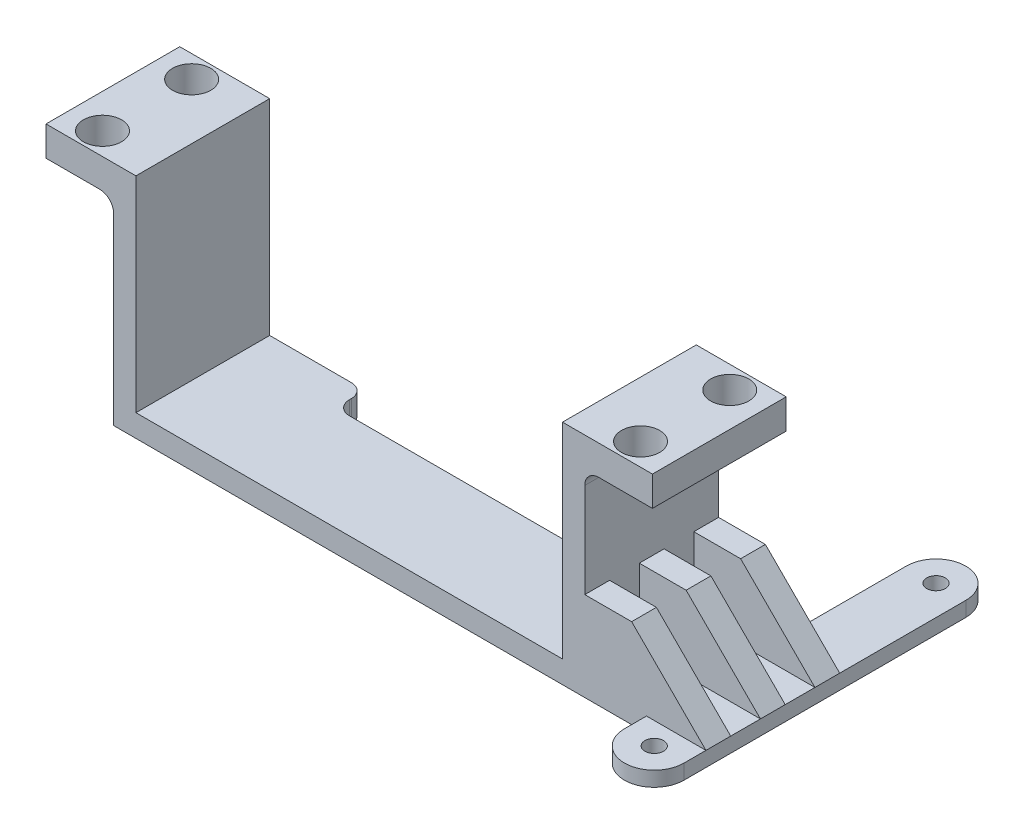
SolidWorks part; units mm, degrees
ref_plane "Front Plane" through (0, 0, 0) normal (0, 0, 1) x (1, 0, 0)
ref_plane "Top Plane" through (0, 0, 0) normal (0, 1, 0) x (1, 0, 0)
ref_plane "Right Plane" through (0, 0, 0) normal (1, 0, 0) x (0, 0, -1)
sketch "Sketch1" plane through (0, 0, 0) normal (0, 0, 1) x (1, 0, 0)
  line L0 (-3.81, 35.052) -> (0, 35.052)
  line L1 (0, 0) -> (72.898, 0)
  line L2 (0, 0) -> (0, 35.052)
  line L4 (72.898, 0) -> (72.898, 35.052)
  line L6 (-3.81, 35.052) -> (-3.81, -3.81)
  line L7 (-3.81, -3.81) -> (76.708, -3.81)
  line L8 (76.708, 35.052) -> (76.708, -3.81)
  line L9 (72.898, 35.052) -> (76.708, 35.052)
  dimension "D1" = 3.81
  dimension "D2" = 3.81
  dimension "D3" = 3.81
  dimension "D4" = 38.862
  dimension "D5" = 72.898
extrude "Boss-Extrude1" add sketch "Sketch1" along normal blind 22.86
sketch "Sketch2" plane through (0, -3.81, 0) normal (0, -1, 0) x (1, 0, 0)
  line L0 (92.329, 26.6192) -> (92.329, -21.5392) construction
  line L2 (87.249, 26.6192) -> (87.249, 22.86)
  line L3 (97.409, 26.6192) -> (97.409, -21.5392)
  line L4 (-3.81, 22.86) -> (76.708, 22.86) construction
  line L5 (76.708, 22.86) -> (76.708, 0) construction
  line L6 (76.708, 22.86) -> (87.249, 22.86)
  line L7 (76.708, 22.86) -> (76.708, 0)
  line L8 (76.708, 0) -> (87.249, 0)
  line L9 (87.249, 0) -> (87.249, -21.5392)
  circle A0 centre (92.329, 26.6192) radius 1.5875
  circle A1 centre (92.329, -21.5392) radius 1.5875
  arc A2 (97.409, 26.6192) -> (87.249, 26.6192) centre (92.329, 26.6192) ccw
  arc A3 (87.249, -21.5392) -> (97.409, -21.5392) centre (92.329, -21.5392) ccw
  point P4 (92.329, 2.54)
  point P5 (76.708, 11.43)
  point P6 (36.449, 22.86)
  point P9 (92.329, 25.0317)
  point P14 (92.329, -19.9517)
  dimension "D2" = 3.175
  dimension "D3" = 5.08
  dimension "D1" = 44.9834
  dimension "D4" = 55.88
  dimension "D5" = 8.89
extrude "Boss-Extrude2" add sketch "Sketch2" against normal blind 2.54 contours L2 A3 L3 A2
sketch "Sketch4" plane through (0, 35.052, 0) normal (0, 1, 0) x (1, 0, 0)
  line L0 (0, -22.86) -> (-3.81, -22.86) construction
  line L1 (0, 0) -> (-15.367, 0)
  line L2 (0, 0) -> (0, -22.86)
  line L3 (0, -22.86) -> (-15.367, -22.86)
  line L4 (-15.367, 0) -> (-15.367, -22.86)
  line L5 (-3.81, -22.86) -> (-3.81, 0) construction
  line L6 (-9.525, -3.81) -> (-9.525, -19.05) construction
  circle A0 centre (-9.525, -3.81) radius 3.2639
  circle A1 centre (-9.525, -19.05) radius 3.2639
  point P13 (-15.367, -11.43)
  point P14 (-9.525, -11.43)
  dimension "D1" = 6.5278
  dimension "D2" = 5.715
  dimension "D3" = 7.62
  dimension "D4" = 5.842
extrude "Boss-Extrude3" add sketch "Sketch4" against normal blind 5.08
ref_plane "Plane1" through (36.449, 0, 0) normal (1, 0, 0) x (0, 0, -1)
mirror "Mirror1" about plane through (36.449, 0, 0) normal (1, 0, 0) of "Boss-Extrude3"
sketch "Sketch5" plane through (0, -1.27, 0) normal (0, 1, 0) x (1, 0, 0)
  line L0 (97.409, 21.5392) -> (97.409, -26.6192) construction
  line L1 (76.708, 0) -> (97.409, 0)
  line L2 (76.708, 0) -> (76.708, -4.2333)
  line L3 (76.708, -4.2333) -> (97.409, -4.2333)
  line L4 (97.409, 0) -> (97.409, -4.2333)
  line L5 (76.708, -22.86) -> (76.708, 0) construction
  line L6 (76.708, -22.86) -> (97.409, -22.86)
  line L7 (76.708, -22.86) -> (76.708, -18.6267)
  line L8 (76.708, -18.6267) -> (97.409, -18.6267)
  line L9 (97.409, -22.86) -> (97.409, -18.6267)
  line L10 (76.708, -9.3133) -> (97.409, -9.3133)
  line L11 (76.708, -9.3133) -> (76.708, -13.5467)
  line L12 (76.708, -13.5467) -> (97.409, -13.5467)
  line L13 (97.409, -9.3133) -> (97.409, -13.5467)
  dimension "D1" = 5.08
  dimension "D2" = 5.08
extrude "Boss-Extrude4" add sketch "Sketch5" along normal blind 12.7
chamfer "Chamfer1" distance 12.7 angle 45 3 edges at (97.409, 11.43, 20.7433) (97.409, 11.43, 11.43) (97.409, 11.43, 2.1167)
fillet "Fillet1" radius 2.38 2 edges at (76.708, 29.972, 11.43) (-3.81, 29.972, 11.43)
sketch "Sketch6" plane through (0, -3.81, 0) normal (0, -1, 0) x (1, 0, 0)
  line L23 (-3.81, 0) -> (87.249, 0) construction
  line L24 (67.1195, 0) -> (16.3195, 0)
  line L25 (67.1195, 0) -> (67.1195, 5.08)
  line L26 (67.1195, 5.08) -> (16.3195, 5.08)
  line L27 (16.3195, 0) -> (16.3195, 5.08)
  point P16 (41.7195, 5.08)
  dimension "D1" = 5.08
extrude "Cut-Extrude1" cut sketch "Sketch6" against normal through all
fillet "Fillet2" radius 2.38 4 edges at (16.3195, -1.905, 0) (67.1195, -1.905, 0) (16.3195, -1.905, 5.08) (67.1195, -1.905, 5.08)
